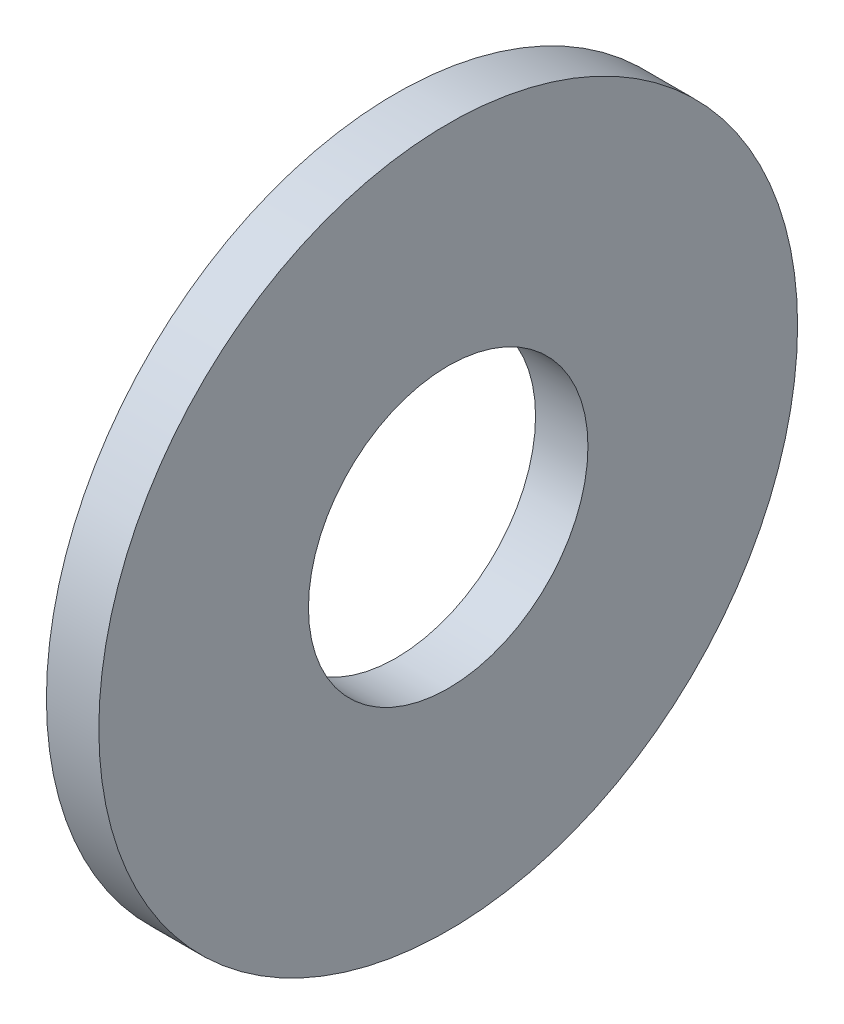
SolidWorks part; units mm, degrees
ref_plane "Front Plane" through (0, 0, 0) normal (0, 0, 1) x (1, 0, 0)
ref_plane "Top Plane" through (0, 0, 0) normal (0, 1, 0) x (1, 0, 0)
ref_plane "Right Plane" through (0, 0, 0) normal (1, 0, 0) x (0, 0, -1)
sketch "Sketch2" plane through (0, 0, 0) normal (1, 0, 0) x (0, 0, -1)
  circle A0 centre (0, 0) radius 0.8
  circle A1 centre (0, 0) radius 2
  dimension "D1" = 4
  dimension "D2" = 1.6
extrude "Boss-Extrude1" add sketch "Sketch2" along normal blind 0.3
